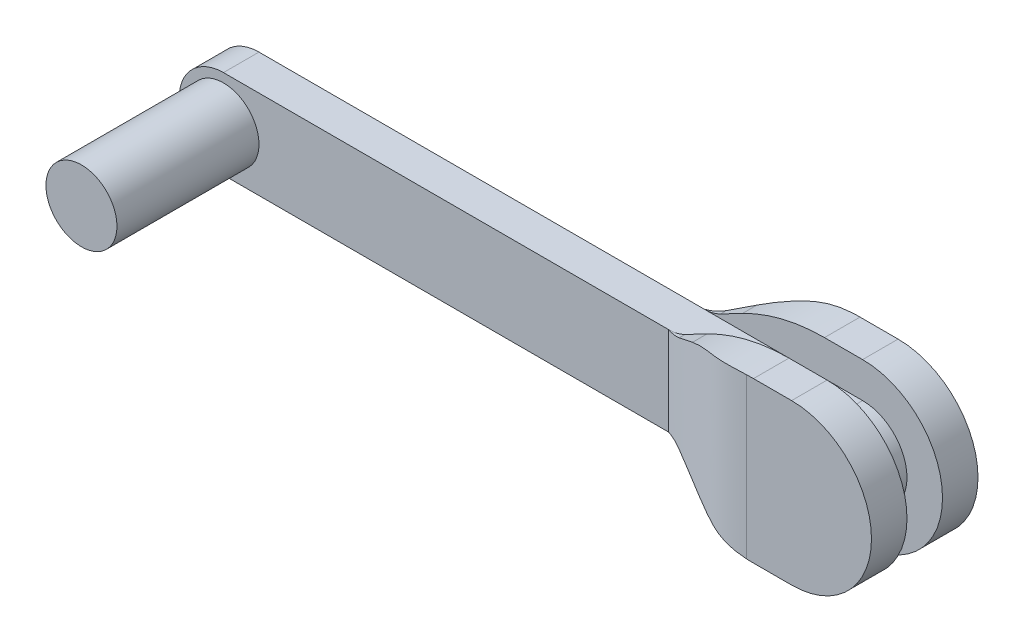
SolidWorks part; units mm, degrees
ref_plane "Front Plane" through (0, 0, 0) normal (0, 0, 1) x (1, 0, 0)
ref_plane "Top Plane" through (0, 0, 0) normal (0, 1, 0) x (1, 0, 0)
ref_plane "Right Plane" through (0, 0, 0) normal (1, 0, 0) x (0, 0, -1)
sketch "Sketch1" plane through (0, 0, 0) normal (0, 0, 1) x (1, 0, 0)
  line L0 (0, -2.5) -> (34, -2.5)
  line L3 (0, 2.5) -> (34, 2.5)
  arc A0 (0, 2.5) -> (0, -2.5) centre (0, 0) ccw
  arc A1 (34, -2.5) -> (34, 2.5) centre (34, 0) ccw
  dimension "D2" = 5
  dimension "D1" = 34
extrude "Boss-Extrude1" add sketch "Sketch1" along normal blind 2
sketch "Sketch2" plane through (0, 0, 2) normal (0, 0, 1) x (1, 0, 0)
  circle A0 centre (0, 0) radius 2
  dimension "D1" = 4
extrude "Boss-Extrude2" add sketch "Sketch2" along normal blind 8
sketch "Sketch5" plane through (0, 0, 0) normal (0, 0, -1) x (-1, 0, 0)
  circle A0 centre (-34, 0) radius 2
  dimension "D1" = 4
extrude "Cut-Extrude2" cut sketch "Sketch5" against normal mid plane 8
sketch "Sketch3" plane through (0, 0, 0) normal (0, 0, -1) x (-1, 0, 0)
  line L0 (-34, -4.5) -> (-31.854, -4.5)
  line L2 (-31.854, 4.5) -> (-34, 4.5)
  line L3 (-27.2347, -3.3692) -> (-26.0001, -2.7262)
  line L5 (-27.2347, 3.3692) -> (-26.0001, 2.7262)
  line L7 (-25.0763, -2.5) -> (-25.0763, 2.5)
  arc A1 (-31.854, -4.5) -> (-27.2347, -3.3692) centre (-31.854, 5.5) ccw
  arc A2 (-34, 4.5) -> (-34, -4.5) centre (-34, 0) ccw
  arc A3 (-34, 4.5) -> (-34, -4.5) centre (-34, 0) ccw
  arc A4 (-27.2347, 3.3692) -> (-31.854, 4.5) centre (-31.854, -5.5) ccw
  arc A5 (-25.0763, 2.5) -> (-26.0001, 2.7262) centre (-25.0763, 4.5) cw
  arc A6 (-25.0763, -2.5) -> (-26.0001, -2.7262) centre (-25.0763, -4.5) ccw
  dimension "D2" = 10
  dimension "D3" = 2
  dimension "D4" = 2
  dimension "D1" = 2
extrude "Boss-Extrude3" add sketch "Sketch3" along normal blind 2
sketch "Sketch4" plane through (0, 0, 0) normal (0, 1, 0) x (1, 0, 0)
  line L0 (31.854, 2) -> (31.854, 3.1743)
  line L1 (31.854, 3.1743) -> (24.3839, 3.1743)
  line L2 (24.3839, 3.1743) -> (25.0763, 0)
  spline S0 degree 3 poles (31.854, 2) (29.9625, 2.0207) (29.1699, 1.6051) (25.9668, 0.2836) (25.0763, 0) knots 0 0 0 0 0.608349 1 1 1 1
extrude "Cut-Extrude1" cut sketch "Sketch4" against normal mid plane 11
ref_plane "Plane1" through (0, 0, 1) normal (0, 0, 1) x (1, 0, 0)
mirror "Mirror1" about plane through (0, 0, 1) normal (0, 0, 1) of "Cut-Extrude1", "Boss-Extrude3"
